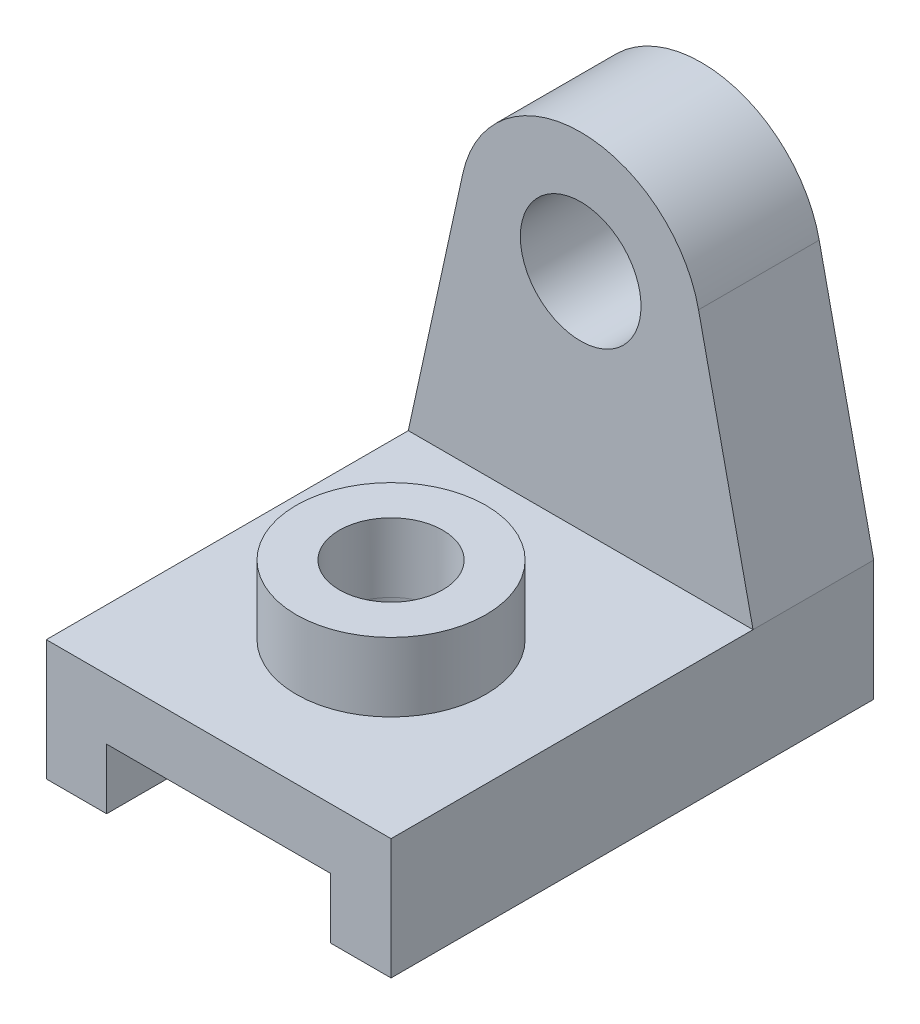
SolidWorks part; units mm, degrees
ref_plane "前视基准面" through (0, 0, 0) normal (0, 0, 1) x (1, 0, 0)
ref_plane "上视基准面" through (0, 0, 0) normal (0, 1, 0) x (1, 0, 0)
ref_plane "右视基准面" through (0, 0, 0) normal (1, 0, 0) x (0, 0, -1)
other "Configuration Table"
sketch "草图1" plane through (0, 0, 0) normal (0, 0, 1) x (1, 0, 0)
  line L4 (-20, 0) -> (20, 0)
  line L5 (20, 0) -> (20, -14)
  line L6 (20, -14) -> (13, -14)
  line L7 (13, -14) -> (13, -7)
  line L8 (13, -7) -> (-13, -7)
  line L9 (0, 11.3103) -> (0, -17.6552) construction
  line L10 (-13, -14) -> (-13, -7)
  line L11 (-20, -14) -> (-13, -14)
  line L12 (-20, 0) -> (-20, -14)
  point P0 (-47.7241, 0.4138)
  point P11 (0, -7)
  point P14 (0, 0)
  dimension "D1" = 20
  dimension "D2" = 7
  dimension "D3" = 13
  dimension "D4" = 7
  dimension "D5" = 14
extrude "凸台-拉伸1" add sketch "草图1" against normal blind 56
sketch "草图2" plane through (0, 0, 0) normal (0, 1, 0) x (1, 0, 0)
  line L1 (20, 0) -> (-20, 0) construction
  circle A0 centre (0, 20) radius 6
  circle A1 centre (0, 20) radius 11
  dimension "D1" = 22
  dimension "D2" = 12
  dimension "D3" = 20
sketch "草图3" plane through (0, 0, -56) normal (0, 0, -1) x (-1, 0, 0)
  line L0 (0, 20.6289) -> (0, -19.0733) construction
  line L1 (-20, 0) -> (20, 0) construction
  line L2 (-13.6784, 28.9834) -> (-20, 0)
  line L3 (13.6784, 28.9834) -> (20, 0)
  circle A0 centre (0, 26) radius 7
  arc A1 (13.6784, 28.9834) -> (-13.6784, 28.9834) centre (0, 26) ccw
  dimension "D1" = 14
  dimension "D2" = 28
  dimension "D3" = 26
extrude "凸台-拉伸2" add sketch "草图3" against normal blind 14
extrude "凸台-拉伸3" add sketch "草图2" along normal blind 8
sketch "草图8" plane through (0, 0, 0) normal (0, 1, 0) x (1, 0, 0)
  circle A0 centre (0, 19.9942) radius 6.0058
  point P2 (0, 0)
extrude "切除-拉伸1" cut sketch "草图8" against normal blind 10 contours A0
